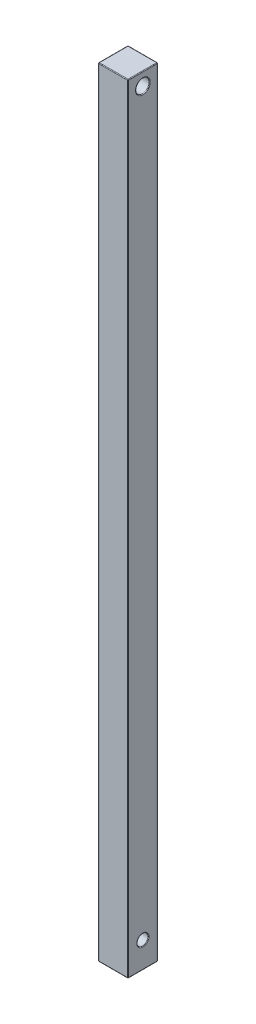
SolidWorks part; units mm, degrees
ref_plane "Front Plane" through (0, 0, 0) normal (0, 0, 1) x (1, 0, 0)
ref_plane "Top Plane" through (0, 0, 0) normal (0, 1, 0) x (1, 0, 0)
ref_plane "Right Plane" through (0, 0, 0) normal (1, 0, 0) x (0, 0, -1)
sketch "Sketch1" plane through (0, 0, 0) normal (0, 1, 0) x (1, 0, 0)
  line L1 (0, 0) -> (23, 0)
  line L2 (0, 0) -> (0, 23)
  line L3 (0, 23) -> (23, 23)
  line L4 (23, 0) -> (23, 23)
  dimension "D1" = 23
  dimension "D2" = 23
extrude "Boss-Extrude1" add sketch "Sketch1" along normal blind 600
sketch "Sketch2" plane through (23, 0, 0) normal (1, 0, 0) x (0, 0, -1)
  line L0 (0, 0) -> (23, 0) construction
  circle A0 centre (11.5, 20) radius 4.25
  point P2 (11.5, 0)
  dimension "D1" = 8.5
  dimension "D2" = 20
extrude "Cut-Extrude1" cut sketch "Sketch2" against normal blind 350
sketch "Sketch3" plane through (23, 0, 0) normal (1, 0, 0) x (0, 0, -1)
  line L0 (0, 600) -> (23, 600) construction
  circle A0 centre (11.5, 590) radius 5.25
  point P4 (11.5, 600)
  dimension "D1" = 10.5
  dimension "D2" = 10
extrude "Cut-Extrude2" cut sketch "Sketch3" against normal blind 49
fillet "Fillet1" radius 0.5 16 edges at (0, 600, -11.5) (0, 0, -11.5) (0, 20, -15.75) (0, 590, -16.75) (11.5, 600, -23) (0, 300, -23) (11.5, 0, -23) (23, 600, -11.5) (23, 300, -23) (23, 0, -11.5) (23, 20, -15.75) (23, 590, -16.75) (0, 300, 0) (11.5, 600, 0) (23, 300, 0) (11.5, 0, 0)
